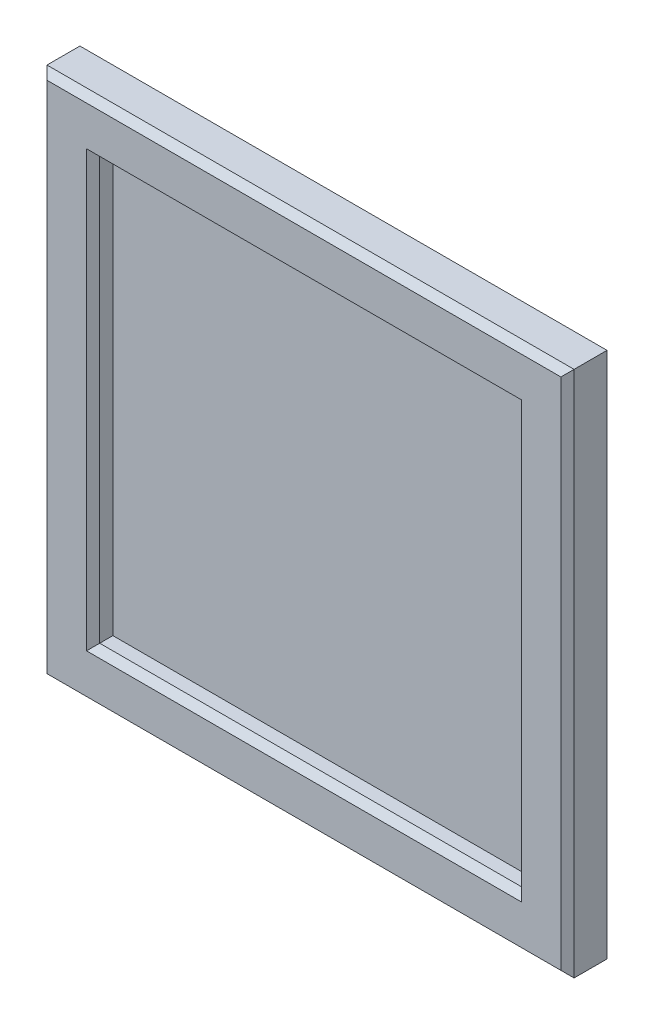
SolidWorks part; units mm, degrees
ref_plane "Спереди" through (0, 0, 0) normal (0, 0, 1) x (1, 0, 0)
ref_plane "Сверху" through (0, 0, 0) normal (0, 1, 0) x (1, 0, 0)
ref_plane "Справа" through (0, 0, 0) normal (1, 0, 0) x (0, 0, -1)
other "Configuration Table"
sketch "Эскиз1" plane through (0, 0, 0) normal (0, 0, 1) x (1, 0, 0)
  line L0 (80, 80) -> (80, 720)
  line L1 (0, 0) -> (800, 0)
  line L2 (0, 0) -> (0, 800)
  line L3 (0, 800) -> (800, 800)
  line L4 (800, 0) -> (800, 800)
  line L5 (80, 720) -> (720, 720)
  line L6 (720, 80) -> (720, 720)
  line L7 (80, 80) -> (720, 80)
  dimension "D1" = 800
  dimension "D2" = 80
extrude "Бобышка-Вытянуть1" add sketch "Эскиз1" along normal blind 60
chamfer "Фаска1" distance 10 angle 45 8 edges at (720, 400, 60) (400, 720, 60) (80, 400, 60) (400, 80, 60) (400, 800, 60) (800, 400, 60) (400, 0, 60) (0, 400, 60)
sketch "Эскиз2" plane through (0, 0, 0) normal (0, 0, -1) x (-1, 0, 0)
  line L1 (-752.9246, 752.0553) -> (-41.8597, 752.0553)
  line L2 (-752.9246, 752.0553) -> (-752.9246, 37.5134)
  line L3 (-752.9246, 37.5134) -> (-41.8597, 37.5134)
  line L4 (-41.8597, 752.0553) -> (-41.8597, 37.5134)
extrude "Бобышка-Вытянуть2" add sketch "Эскиз2" against normal blind 10 from offset 20 separate body
